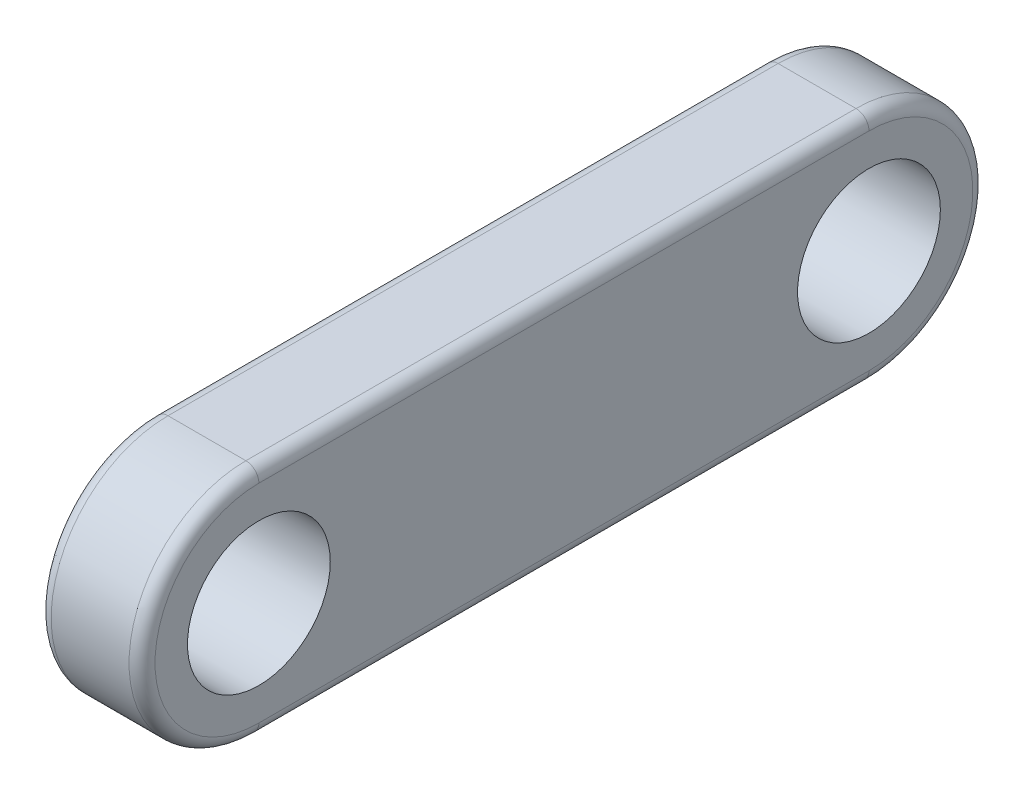
SolidWorks part; units mm, degrees
ref_plane "Alzado" through (0, 0, 0) normal (1, 0, 0) x (0, 1, 0)
ref_plane "Planta" through (0, 0, 0) normal (0, 0, 1) x (0, 1, 0)
ref_plane "Vista lateral" through (0, 0, 0) normal (0, 1, 0) x (-1, 0, 0)
sketch "Croquis1" plane through (0, 0, 0) normal (1, 0, 0) x (0, 1, 0)
  line L0 (-4.5, 32.5) -> (-4.5, 0)
  line L1 (-4.5, 32.5) -> (4.5, 32.5)
  line L2 (-4.5, 0) -> (4.5, 0)
  line L3 (4.5, 32.5) -> (4.5, 0)
  line L4 (-4.5, 32.5) -> (4.5, 0) construction
  line L5 (-4.5, 0) -> (4.5, 32.5) construction
  line L8 (-4.5, 15) -> (-4.5, 9)
  line L10 (4.5, 15) -> (4.5, 9)
  circle A0 centre (0, 4.5) radius 2.75
  circle A1 centre (0, 28) radius 2.75
  arc A2 (0, 32.5) -> (-4.5, 28) centre (0, 28) ccw
  arc A3 (0, 0) -> (4.5, 4.5) centre (0, 4.5) ccw
  arc A4 (4.5, 28) -> (0, 32.5) centre (0, 28) ccw
  arc A5 (-4.5, 4.5) -> (0, 0) centre (0, 4.5) ccw
  point P0 (0, 0)
  point P1 (0, 16.25)
  dimension "D1" = 5.5
  dimension "D3" = 23.5
  dimension "D4" = 4.5
  dimension "D5" = 4.5
  dimension "D2" = 4.5
extrude "Saliente-Extruir4" add sketch "Croquis1" along normal mid plane 4 contours L0 A5 L2 A3 L3 A4 L1 A2 A1 A0
fillet "Redondeo1" radius 0.5 8 edges at (2, 0, 32.5) (2, 4.5, 16.25) (2, 0, 0) (-2, 0, 32.5) (-2, -4.5, 16.25) (-2, 0, 0) (2, -4.5, 16.25) (-2, 4.5, 16.25)
equation "\"D5@Croquis1\"=\"D4@Croquis1\""
